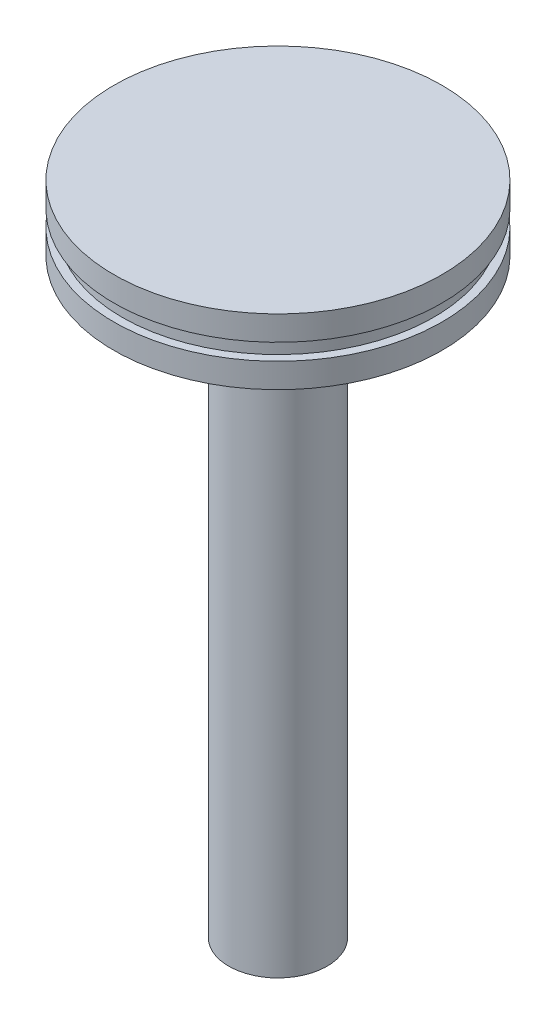
SolidWorks part; units mm, degrees
ref_plane "Plan de face" through (0, 0, 0) normal (0, 0, 1) x (1, 0, 0)
ref_plane "Plan de dessus" through (0, 0, 0) normal (0, 1, 0) x (1, 0, 0)
ref_plane "Plan de droite" through (0, 0, 0) normal (1, 0, 0) x (0, 0, -1)
sketch "Esquisse1" plane through (0, 0, 0) normal (0, 0, 1) x (1, 0, 0)
  line L0 (0, 0) -> (0, 20) construction
  line L1 (0, 20) -> (5, 20)
  line L2 (5, 20) -> (5, 19.25)
  line L3 (5, 18) -> (1.5, 18)
  line L4 (1.5, 18) -> (1.5, 0)
  line L5 (1.5, 0) -> (0, 0)
  line L6 (5, 19.25) -> (4.75, 19.25)
  line L7 (4.75, 19.25) -> (4.75, 18.75)
  line L8 (4.75, 18.75) -> (5, 18.75)
  line L9 (5, 18.75) -> (5, 18)
  line L10 (0, 20) -> (0, 0)
  dimension "D1" = 20
  dimension "D2" = 2
  dimension "D3" = 0.75
  dimension "D4" = 0.75
  dimension "D5" = 10
  dimension "D6" = 9.5
  dimension "D7" = 3
revolve "Révolution1" add sketch "Esquisse1" angle 360 about L0
fillet "Congé1" radius 0.5 1 edges at (0, 18, -1.5)
scale "Echelle1" scale about centroid uniform scaling yes scale factor 0.578571
